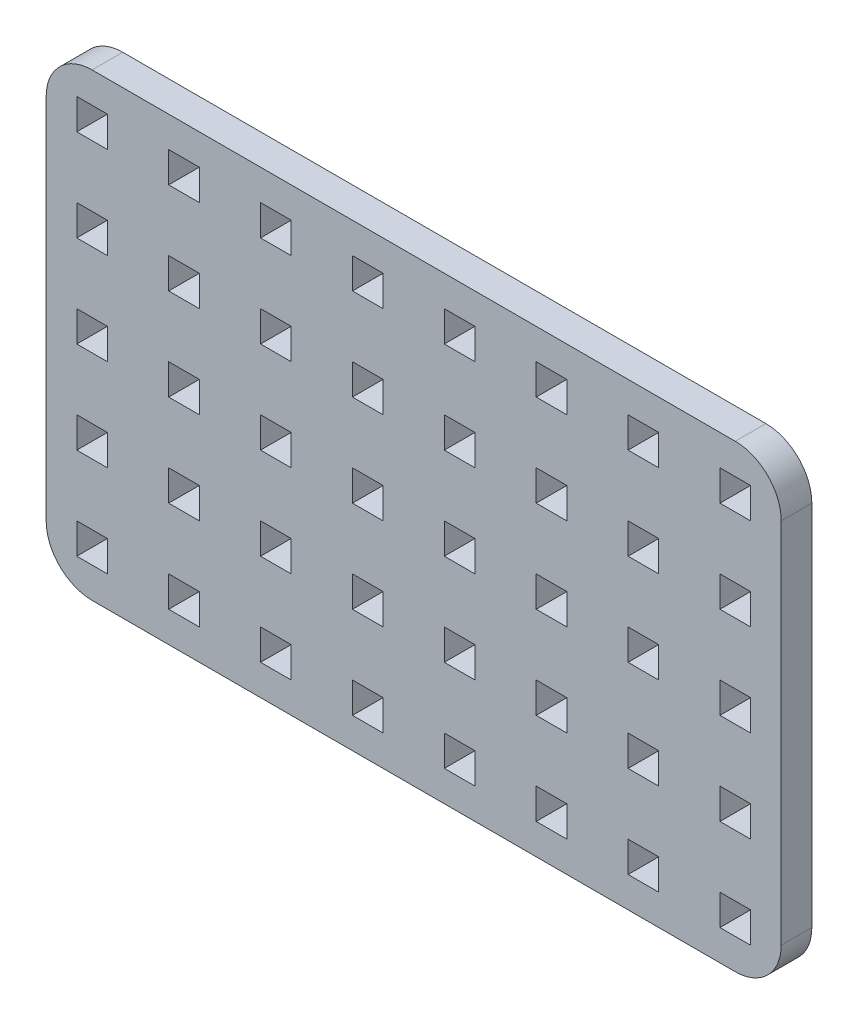
SolidWorks part; units mm, degrees
ref_plane "Alzado" through (0, 0, 0) normal (0, 0, 1) x (1, 0, 0)
ref_plane "Planta" through (0, 0, 0) normal (0, 1, 0) x (1, 0, 0)
ref_plane "Vista lateral" through (0, 0, 0) normal (1, 0, 0) x (0, 0, -1)
sketch "Model" plane through (0, 0, 0) normal (0, 0, 1) x (1, 0, 0)
  line L0 (8.4202, 297.2418) -> (8.4202, 294.2418)
  line L1 (11.4202, 297.2418) -> (8.4202, 297.2418)
  line L2 (11.4202, 294.2418) -> (11.4202, 297.2418)
  line L3 (8.4202, 294.2418) -> (11.4202, 294.2418)
  line L4 (17.4202, 297.2418) -> (17.4202, 294.2418)
  line L5 (20.4202, 297.2418) -> (17.4202, 297.2418)
  line L6 (20.4202, 294.2418) -> (20.4202, 297.2418)
  line L7 (17.4202, 294.2418) -> (20.4202, 294.2418)
  line L8 (26.4202, 297.2418) -> (26.4202, 294.2418)
  line L9 (29.4202, 297.2418) -> (26.4202, 297.2418)
  line L10 (29.4202, 294.2418) -> (29.4202, 297.2418)
  line L11 (26.4202, 294.2418) -> (29.4202, 294.2418)
  line L12 (35.4202, 297.2418) -> (35.4202, 294.2418)
  line L13 (38.4202, 297.2418) -> (35.4202, 297.2418)
  line L14 (38.4202, 294.2418) -> (38.4202, 297.2418)
  line L15 (35.4202, 294.2418) -> (38.4202, 294.2418)
  line L16 (44.4202, 297.2418) -> (44.4202, 294.2418)
  line L17 (47.4202, 297.2418) -> (44.4202, 297.2418)
  line L18 (47.4202, 294.2418) -> (47.4202, 297.2418)
  line L19 (44.4202, 294.2418) -> (47.4202, 294.2418)
  line L20 (53.4202, 297.2418) -> (53.4202, 294.2418)
  line L21 (56.4202, 297.2418) -> (53.4202, 297.2418)
  line L22 (56.4202, 294.2418) -> (56.4202, 297.2418)
  line L23 (53.4202, 294.2418) -> (56.4202, 294.2418)
  line L24 (62.4202, 297.2418) -> (62.4202, 294.2418)
  line L25 (65.4202, 297.2418) -> (62.4202, 297.2418)
  line L26 (65.4202, 294.2418) -> (65.4202, 297.2418)
  line L27 (62.4202, 294.2418) -> (65.4202, 294.2418)
  line L28 (71.4202, 297.2418) -> (71.4202, 294.2418)
  line L29 (74.4202, 297.2418) -> (71.4202, 297.2418)
  line L30 (74.4202, 294.2418) -> (74.4202, 297.2418)
  line L31 (71.4202, 294.2418) -> (74.4202, 294.2418)
  line L32 (8.4202, 261.2418) -> (8.4202, 258.2418)
  line L33 (11.4202, 261.2418) -> (8.4202, 261.2418)
  line L34 (11.4202, 258.2418) -> (11.4202, 261.2418)
  line L35 (8.4202, 258.2418) -> (11.4202, 258.2418)
  line L36 (17.4202, 261.2418) -> (17.4202, 258.2418)
  line L37 (20.4202, 261.2418) -> (17.4202, 261.2418)
  line L38 (20.4202, 258.2418) -> (20.4202, 261.2418)
  line L39 (17.4202, 258.2418) -> (20.4202, 258.2418)
  line L40 (26.4202, 261.2418) -> (26.4202, 258.2418)
  line L41 (29.4202, 261.2418) -> (26.4202, 261.2418)
  line L42 (29.4202, 258.2418) -> (29.4202, 261.2418)
  line L43 (26.4202, 258.2418) -> (29.4202, 258.2418)
  line L44 (35.4202, 261.2418) -> (35.4202, 258.2418)
  line L45 (38.4202, 261.2418) -> (35.4202, 261.2418)
  line L46 (38.4202, 258.2418) -> (38.4202, 261.2418)
  line L47 (35.4202, 258.2418) -> (38.4202, 258.2418)
  line L48 (44.4202, 261.2418) -> (44.4202, 258.2418)
  line L49 (47.4202, 261.2418) -> (44.4202, 261.2418)
  line L50 (47.4202, 258.2418) -> (47.4202, 261.2418)
  line L51 (44.4202, 258.2418) -> (47.4202, 258.2418)
  line L52 (53.4202, 261.2418) -> (53.4202, 258.2418)
  line L53 (56.4202, 261.2418) -> (53.4202, 261.2418)
  line L54 (56.4202, 258.2418) -> (56.4202, 261.2418)
  line L55 (53.4202, 258.2418) -> (56.4202, 258.2418)
  line L56 (62.4202, 261.2418) -> (62.4202, 258.2418)
  line L57 (65.4202, 261.2418) -> (62.4202, 261.2418)
  line L58 (65.4202, 258.2418) -> (65.4202, 261.2418)
  line L59 (62.4202, 258.2418) -> (65.4202, 258.2418)
  line L60 (71.4202, 261.2418) -> (71.4202, 258.2418)
  line L61 (74.4202, 261.2418) -> (71.4202, 261.2418)
  line L62 (74.4202, 258.2418) -> (74.4202, 261.2418)
  line L63 (71.4202, 258.2418) -> (74.4202, 258.2418)
  line L64 (71.4202, 288.2418) -> (71.4202, 285.2418)
  line L65 (74.4202, 288.2418) -> (71.4202, 288.2418)
  line L66 (74.4202, 285.2418) -> (74.4202, 288.2418)
  line L67 (71.4202, 285.2418) -> (74.4202, 285.2418)
  line L68 (71.4202, 270.2418) -> (71.4202, 267.2418)
  line L69 (74.4202, 270.2418) -> (71.4202, 270.2418)
  line L70 (74.4202, 267.2418) -> (74.4202, 270.2418)
  line L71 (71.4202, 267.2418) -> (74.4202, 267.2418)
  line L72 (71.4202, 279.2418) -> (71.4202, 276.2418)
  line L73 (74.4202, 279.2418) -> (71.4202, 279.2418)
  line L74 (74.4202, 276.2418) -> (74.4202, 279.2418)
  line L75 (71.4202, 276.2418) -> (74.4202, 276.2418)
  line L76 (8.4202, 288.2418) -> (8.4202, 285.2418)
  line L77 (11.4202, 288.2418) -> (8.4202, 288.2418)
  line L78 (11.4202, 285.2418) -> (11.4202, 288.2418)
  line L79 (8.4202, 285.2418) -> (11.4202, 285.2418)
  line L80 (8.4202, 270.2418) -> (8.4202, 267.2418)
  line L81 (11.4202, 270.2418) -> (8.4202, 270.2418)
  line L82 (11.4202, 267.2418) -> (11.4202, 270.2418)
  line L83 (8.4202, 267.2418) -> (11.4202, 267.2418)
  line L84 (8.4202, 279.2418) -> (8.4202, 276.2418)
  line L85 (11.4202, 279.2418) -> (8.4202, 279.2418)
  line L86 (11.4202, 276.2418) -> (11.4202, 279.2418)
  line L87 (8.4202, 276.2418) -> (11.4202, 276.2418)
  line L88 (17.4202, 270.2418) -> (17.4202, 267.2418)
  line L89 (20.4202, 270.2418) -> (17.4202, 270.2418)
  line L90 (20.4202, 267.2418) -> (20.4202, 270.2418)
  line L91 (17.4202, 267.2418) -> (20.4202, 267.2418)
  line L92 (26.4202, 270.2418) -> (26.4202, 267.2418)
  line L93 (29.4202, 270.2418) -> (26.4202, 270.2418)
  line L94 (29.4202, 267.2418) -> (29.4202, 270.2418)
  line L95 (26.4202, 267.2418) -> (29.4202, 267.2418)
  line L96 (35.4202, 270.2418) -> (35.4202, 267.2418)
  line L97 (38.4202, 270.2418) -> (35.4202, 270.2418)
  line L98 (38.4202, 267.2418) -> (38.4202, 270.2418)
  line L99 (35.4202, 267.2418) -> (38.4202, 267.2418)
  line L100 (62.4202, 270.2418) -> (62.4202, 267.2418)
  line L101 (65.4202, 270.2418) -> (62.4202, 270.2418)
  line L102 (65.4202, 267.2418) -> (65.4202, 270.2418)
  line L103 (62.4202, 267.2418) -> (65.4202, 267.2418)
  line L104 (44.4202, 270.2418) -> (44.4202, 267.2418)
  line L105 (47.4202, 270.2418) -> (44.4202, 270.2418)
  line L106 (47.4202, 267.2418) -> (47.4202, 270.2418)
  line L107 (44.4202, 267.2418) -> (47.4202, 267.2418)
  line L108 (53.4202, 270.2418) -> (53.4202, 267.2418)
  line L109 (56.4202, 270.2418) -> (53.4202, 270.2418)
  line L110 (56.4202, 267.2418) -> (56.4202, 270.2418)
  line L111 (53.4202, 267.2418) -> (56.4202, 267.2418)
  line L112 (17.4202, 279.2418) -> (17.4202, 276.2418)
  line L113 (20.4202, 279.2418) -> (17.4202, 279.2418)
  line L114 (20.4202, 276.2418) -> (20.4202, 279.2418)
  line L115 (17.4202, 276.2418) -> (20.4202, 276.2418)
  line L116 (26.4202, 279.2418) -> (26.4202, 276.2418)
  line L117 (29.4202, 279.2418) -> (26.4202, 279.2418)
  line L118 (29.4202, 276.2418) -> (29.4202, 279.2418)
  line L119 (26.4202, 276.2418) -> (29.4202, 276.2418)
  line L120 (35.4202, 279.2418) -> (35.4202, 276.2418)
  line L121 (38.4202, 279.2418) -> (35.4202, 279.2418)
  line L122 (38.4202, 276.2418) -> (38.4202, 279.2418)
  line L123 (35.4202, 276.2418) -> (38.4202, 276.2418)
  line L124 (62.4202, 279.2418) -> (62.4202, 276.2418)
  line L125 (65.4202, 279.2418) -> (62.4202, 279.2418)
  line L126 (65.4202, 276.2418) -> (65.4202, 279.2418)
  line L127 (62.4202, 276.2418) -> (65.4202, 276.2418)
  line L128 (17.4202, 288.2418) -> (17.4202, 285.2418)
  line L129 (20.4202, 288.2418) -> (17.4202, 288.2418)
  line L130 (20.4202, 285.2418) -> (20.4202, 288.2418)
  line L131 (17.4202, 285.2418) -> (20.4202, 285.2418)
  line L132 (26.4202, 288.2418) -> (26.4202, 285.2418)
  line L133 (29.4202, 288.2418) -> (26.4202, 288.2418)
  line L134 (29.4202, 285.2418) -> (29.4202, 288.2418)
  line L135 (26.4202, 285.2418) -> (29.4202, 285.2418)
  line L136 (35.4202, 288.2418) -> (35.4202, 285.2418)
  line L137 (38.4202, 288.2418) -> (35.4202, 288.2418)
  line L138 (38.4202, 285.2418) -> (38.4202, 288.2418)
  line L139 (35.4202, 285.2418) -> (38.4202, 285.2418)
  line L140 (62.4202, 288.2418) -> (62.4202, 285.2418)
  line L141 (65.4202, 288.2418) -> (62.4202, 288.2418)
  line L142 (65.4202, 285.2418) -> (65.4202, 288.2418)
  line L143 (62.4202, 285.2418) -> (65.4202, 285.2418)
  line L144 (44.4202, 279.2418) -> (44.4202, 276.2418)
  line L145 (47.4202, 279.2418) -> (44.4202, 279.2418)
  line L146 (47.4202, 276.2418) -> (47.4202, 279.2418)
  line L147 (44.4202, 276.2418) -> (47.4202, 276.2418)
  line L148 (53.4202, 279.2418) -> (53.4202, 276.2418)
  line L149 (56.4202, 279.2418) -> (53.4202, 279.2418)
  line L150 (56.4202, 276.2418) -> (56.4202, 279.2418)
  line L151 (53.4202, 276.2418) -> (56.4202, 276.2418)
  line L152 (44.4202, 288.2418) -> (44.4202, 285.2418)
  line L153 (47.4202, 288.2418) -> (44.4202, 288.2418)
  line L154 (47.4202, 285.2418) -> (47.4202, 288.2418)
  line L155 (44.4202, 285.2418) -> (47.4202, 285.2418)
  line L156 (53.4202, 288.2418) -> (53.4202, 285.2418)
  line L157 (56.4202, 288.2418) -> (53.4202, 288.2418)
  line L158 (56.4202, 285.2418) -> (56.4202, 288.2418)
  line L159 (53.4202, 285.2418) -> (56.4202, 285.2418)
  line L160 (77.4202, 259.7418) -> (77.4202, 295.7418)
  line L161 (72.9202, 300.2418) -> (9.9202, 300.2418)
  line L162 (5.4202, 295.7418) -> (5.4202, 259.7418)
  line L163 (9.9202, 255.2418) -> (72.9202, 255.2418)
  arc A0 (77.4202, 295.7418) -> (72.9202, 300.2418) centre (72.9202, 295.7418) ccw
  arc A1 (72.9202, 255.2418) -> (77.4202, 259.7418) centre (72.9202, 259.7418) ccw
  arc A2 (9.9202, 300.2418) -> (5.4202, 295.7418) centre (9.9202, 295.7418) ccw
  arc A3 (5.4202, 259.7418) -> (9.9202, 255.2418) centre (9.9202, 259.7418) ccw
extrude "Saliente-Extruir1" add sketch "Model" along normal blind 3
